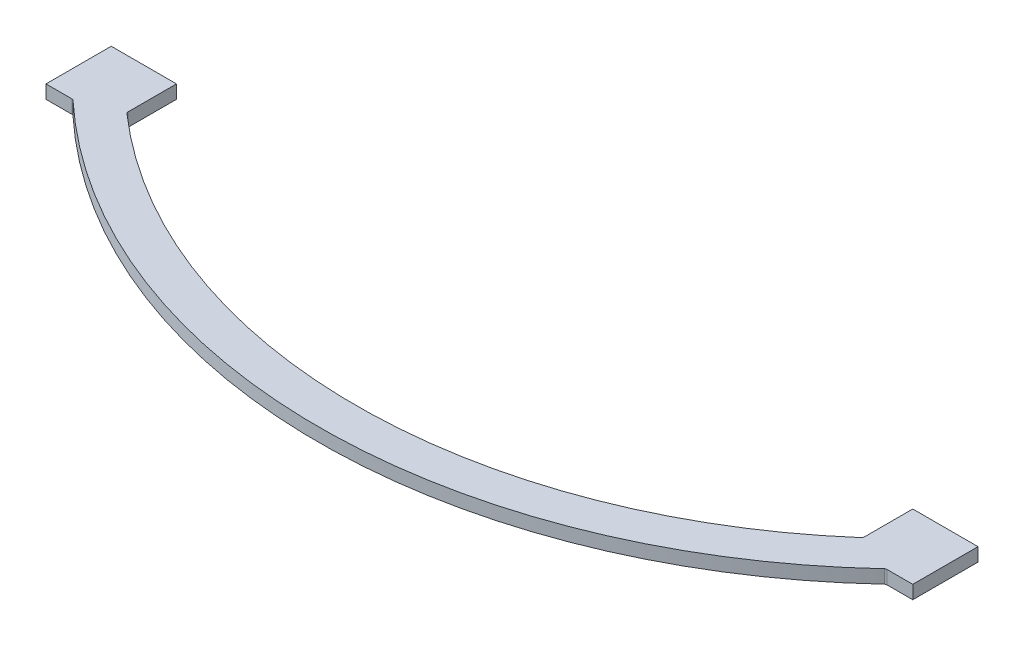
SolidWorks part; units mm, degrees
material "Pine"
ref_plane "Front Plane" through (0, 0, 0) normal (0, 0, 1) x (1, 0, 0)
ref_plane "Top Plane" through (0, 0, 0) normal (0, 1, 0) x (1, 0, 0)
ref_plane "Right Plane" through (0, 0, 0) normal (1, 0, 0) x (0, 0, -1)
sketch "Sketch1" plane through (0, 0, 0) normal (0, 1, 0) x (1, 0, 0)
  line L0 (844.55, 590.55) -> (844.55, -590.55)
  line L1 (-590.55, 862.0125) -> (590.55, 862.0125)
  line L2 (-590.55, 862.0125) -> (-590.55, -862.0125)
  line L3 (-590.55, -862.0125) -> (590.55, -862.0125)
  line L4 (590.55, 862.0125) -> (590.55, -862.0125)
  line L5 (-590.55, 862.0125) -> (590.55, -862.0125) construction
  line L6 (-590.55, -862.0125) -> (590.55, 862.0125) construction
  line L7 (-862.0125, -590.55) -> (862.0125, -590.55)
  line L8 (-862.0125, -590.55) -> (-862.0125, 590.55)
  line L9 (-862.0125, 590.55) -> (862.0125, 590.55)
  line L10 (862.0125, -590.55) -> (862.0125, 590.55)
  line L11 (-862.0125, -590.55) -> (862.0125, 590.55) construction
  line L12 (-862.0125, 590.55) -> (862.0125, -590.55) construction
  circle A0 centre (0, 0) radius 809.625
  circle A1 centre (0, 0) radius 758.825
  dimension "D1" = 1619.25
  dimension "D2" = 50.8
  dimension "D3" = 1181.1
  dimension "D4" = 862.0125
  dimension "D5" = 17.4625
sketch "Sketch2" plane through (0, 0, 0) normal (0, 1, 0) x (1, 0, 0)
  line L0 (546.1, -501.65) -> (546.1, -590.55) construction
  line L13 (590.55, -590.55) -> (501.65, -590.55)
  line L14 (590.55, -590.55) -> (590.55, -501.65)
  line L15 (590.55, -501.65) -> (501.65, -501.65)
  line L16 (501.65, -590.55) -> (501.65, -501.65)
  line L17 (590.55, 862.0125) -> (590.55, -862.0125) construction
  line L18 (501.65, -546.1) -> (590.55, -546.1) construction
  line L19 (-862.0125, -590.55) -> (862.0125, -590.55) construction
  line L20 (-501.65, -590.55) -> (-501.65, -501.65)
  line L21 (-590.55, -501.65) -> (-501.65, -501.65)
  line L22 (-590.55, -590.55) -> (-590.55, -501.65)
  line L23 (-590.55, -590.55) -> (-501.65, -590.55)
  line L24 (-501.65, -546.1) -> (-590.55, -546.1) construction
  line L25 (-546.1, -501.65) -> (-546.1, -590.55) construction
  line L26 (-590.55, 501.65) -> (-501.65, 501.65)
  line L27 (-501.65, 590.55) -> (-501.65, 501.65)
  line L28 (-590.55, 590.55) -> (-501.65, 590.55)
  line L29 (-590.55, 590.55) -> (-590.55, 501.65)
  line L30 (-546.1, 501.65) -> (-546.1, 590.55) construction
  line L31 (-501.65, 546.1) -> (-590.55, 546.1) construction
  line L32 (501.65, 590.55) -> (501.65, 501.65)
  line L33 (590.55, 501.65) -> (501.65, 501.65)
  line L34 (590.55, 590.55) -> (590.55, 501.65)
  line L35 (590.55, 590.55) -> (501.65, 590.55)
  line L36 (501.65, 546.1) -> (590.55, 546.1) construction
  line L37 (546.1, 501.65) -> (546.1, 590.55) construction
  circle A0 centre (0, 0) radius 784.225
  circle A1 centre (0, 0) radius 758.825 construction
  circle A2 centre (0, 0) radius 784.225
  circle A3 centre (0, 0) radius 784.225
  circle A4 centre (0, 0) radius 784.225
  point P24 (546.1, -546.1)
  point P48 (0, 0)
  dimension "D2" = 25.4
  dimension "D1" = 88.9
  dimension "D3" = 4
sketch "Sketch3" plane through (0, 0, 0) normal (0, 1, 0) x (1, 0, 0)
  line L0 (-501.65, -501.65) -> (-590.55, -590.55)
  line L1 (501.65, -501.65) -> (590.55, -590.55)
  line L2 (-590.55, -590.55) -> (-553.8441, -590.55)
  line L3 (-862.0125, -590.55) -> (862.0125, -590.55) construction
  line L4 (590.55, -590.55) -> (553.8441, -590.55)
  line L5 (501.65, -501.65) -> (501.65, -569.3528)
  line L6 (501.65, -590.55) -> (501.65, -501.65) construction
  line L7 (-501.65, -501.65) -> (-501.65, -569.3528)
  circle A0 centre (0, 0) radius 758.825 construction
  circle A1 centre (0, 0) radius 809.625 construction
  arc A2 (-501.65, -569.3528) -> (501.65, -569.3528) centre (0, 0) ccw
  arc A3 (-553.8441, -590.55) -> (553.8441, -590.55) centre (0, 0) ccw
extrude "Boss-Extrude1" add sketch "Sketch3" along normal blind 18.2562
sketch "Sketch4" plane through (0, 18.2562, 0) normal (0, 1, 0) x (1, 0, 0)
  line L0 (-590.55, -590.55) -> (-590.55, -501.65)
  line L1 (-590.55, -501.65) -> (-501.65, -501.65)
  line L2 (-501.65, -501.65) -> (-501.65, -590.55)
  line L3 (-501.65, -590.55) -> (-590.55, -590.55)
  line L4 (501.65, -590.55) -> (501.65, -501.65)
  line L5 (501.65, -501.65) -> (590.55, -501.65)
  line L6 (590.55, -501.65) -> (590.55, -590.55)
  line L7 (590.55, -590.55) -> (501.65, -590.55)
extrude "Boss-Extrude2" add sketch "Sketch4" against normal up to surface (18.2562 mm away) up to face at (0, 0, 614.0941)
fillet "Fillet1" radius 3.3782 4 edges at (501.65, 9.1281, 569.3528) (553.8441, 9.1281, 590.55) (-553.8441, 9.1281, 590.55) (-501.65, 9.1281, 569.3528)
